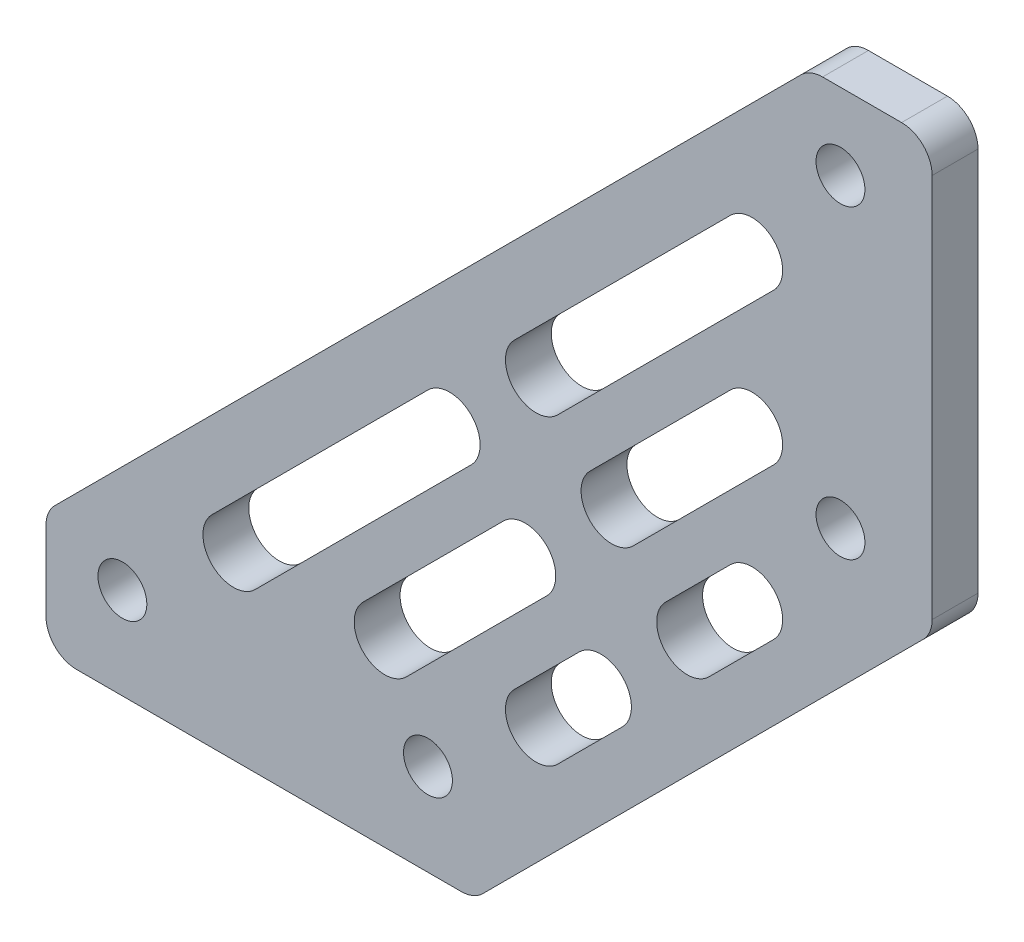
SolidWorks part; units mm, degrees
material "Thornel Mat VMA"
ref_plane "前视基准面" through (0, 0, 0) normal (0, 0, 1) x (1, 0, 0)
ref_plane "上视基准面" through (0, 0, 0) normal (0, 1, 0) x (1, 0, 0)
ref_plane "右视基准面" through (0, 0, 0) normal (1, 0, 0) x (0, 0, -1)
sketch "草图1" plane through (0, 0, 0) normal (0, 0, 1) x (1, 0, 0)
  line L0 (0, 0) -> (28, 0)
  line L1 (28, 0) -> (58, 30)
  line L2 (58, 30) -> (58, 58)
  line L3 (58, 58) -> (50, 58)
  line L4 (50, 58) -> (0, 8)
  line L5 (0, 8) -> (0, 0)
  line L6 (43, 15) -> (25, 33) construction
  circle A0 centre (5, 6) radius 1.6
  circle A1 centre (25, 6) radius 1.6
  circle A2 centre (52, 53) radius 1.6
  circle A3 centre (52, 33) radius 1.6
  point P11 (0, 0)
  point P14 (38.6825, 0)
  dimension "D4" = 3.2
  dimension "D1" = 45
  dimension "D2" = 8
  dimension "D3" = 6
  dimension "D5" = 53
  dimension "D6" = 20
  dimension "D7" = 5
  dimension "D8" = 3
extrude "凸台-拉伸1" add sketch "草图1" along normal blind 3
fillet "圆角1" radius 2 6 edges at (28, 0, 1.5) (0, 0, 1.5) (0, 8, 1.5) (58, 30, 1.5) (58, 58, 1.5) (50, 58, 1.5)
sketch "草图2" plane through (0, 0, 3) normal (0, 0, 1) x (1, 0, 0)
  line L0 (12.2721, 11.7868) -> (26.4142, 25.9289) construction
  line L1 (10.8579, 13.201) -> (25, 27.3431)
  line L2 (13.6863, 10.3726) -> (27.8284, 24.5147)
  line L3 (49.4142, 57.4142) -> (0.5858, 8.5858) construction
  line L4 (25, 33) -> (43, 15) construction
  line L5 (28.5858, 0.5858) -> (57.4142, 29.4142) construction
  line L6 (31.364, 20.9792) -> (22.1716, 11.7868) construction
  line L7 (32.7782, 19.565) -> (23.5858, 10.3726)
  line L8 (29.9497, 22.3934) -> (20.7574, 13.201)
  line L9 (26.4142, 25.9289) -> (31.364, 20.9792) construction
  line L10 (22.1716, 11.7868) -> (12.2721, 11.7868) construction
  line L11 (32.0711, 11.7868) -> (36.3137, 16.0294) construction
  line L12 (30.6569, 13.201) -> (34.8995, 17.4437)
  line L13 (33.4853, 10.3726) -> (37.7279, 14.6152)
  line L14 (36.3137, 16.0294) -> (31.364, 20.9792) construction
  line L15 (46.2132, 45.7279) -> (32.0711, 31.5858) construction
  line L16 (44.799, 47.1421) -> (30.6569, 33)
  line L17 (47.6274, 44.3137) -> (33.4853, 30.1716)
  line L18 (37.0208, 26.636) -> (46.2132, 35.8284) construction
  line L19 (38.435, 25.2218) -> (47.6274, 34.4142)
  line L20 (35.6066, 28.0503) -> (44.799, 37.2426)
  line L21 (46.2132, 25.9289) -> (41.9706, 21.6863) construction
  line L22 (44.799, 27.3431) -> (40.5563, 23.1005)
  line L23 (47.6274, 24.5147) -> (43.3848, 20.2721)
  arc A0 (10.8579, 13.201) -> (13.6863, 10.3726) centre (12.2721, 11.7868) ccw
  arc A1 (27.8284, 24.5147) -> (25, 27.3431) centre (26.4142, 25.9289) ccw
  arc A2 (32.7782, 19.565) -> (29.9497, 22.3934) centre (31.364, 20.9792) ccw
  arc A3 (20.7574, 13.201) -> (23.5858, 10.3726) centre (22.1716, 11.7868) ccw
  arc A4 (30.6569, 13.201) -> (33.4853, 10.3726) centre (32.0711, 11.7868) ccw
  arc A5 (37.7279, 14.6152) -> (34.8995, 17.4437) centre (36.3137, 16.0294) ccw
  arc A6 (44.799, 47.1421) -> (47.6274, 44.3137) centre (46.2132, 45.7279) cw
  arc A7 (33.4853, 30.1716) -> (30.6569, 33) centre (32.0711, 31.5858) cw
  arc A8 (38.435, 25.2218) -> (35.6066, 28.0503) centre (37.0208, 26.636) cw
  arc A9 (44.799, 37.2426) -> (47.6274, 34.4142) centre (46.2132, 35.8284) cw
  arc A10 (44.799, 27.3431) -> (47.6274, 24.5147) centre (46.2132, 25.9289) cw
  arc A11 (43.3848, 20.2721) -> (40.5563, 23.1005) centre (41.9706, 21.6863) cw
  point P2 (19.3431, 18.8579)
  point P15 (26.7678, 16.383)
  point P26 (34.1924, 13.9081)
  point P32 (0, 0)
  point P35 (39.1421, 38.6569)
  point P42 (41.617, 31.2322)
  point P49 (44.0919, 23.8076)
  dimension "D1" = 2
  dimension "D2" = 6
  dimension "D3" = 8
  dimension "D4" = 20
  dimension "D5" = 7
  dimension "D6" = 7
extrude "切除-拉伸1" cut sketch "草图2" against normal blind 10
